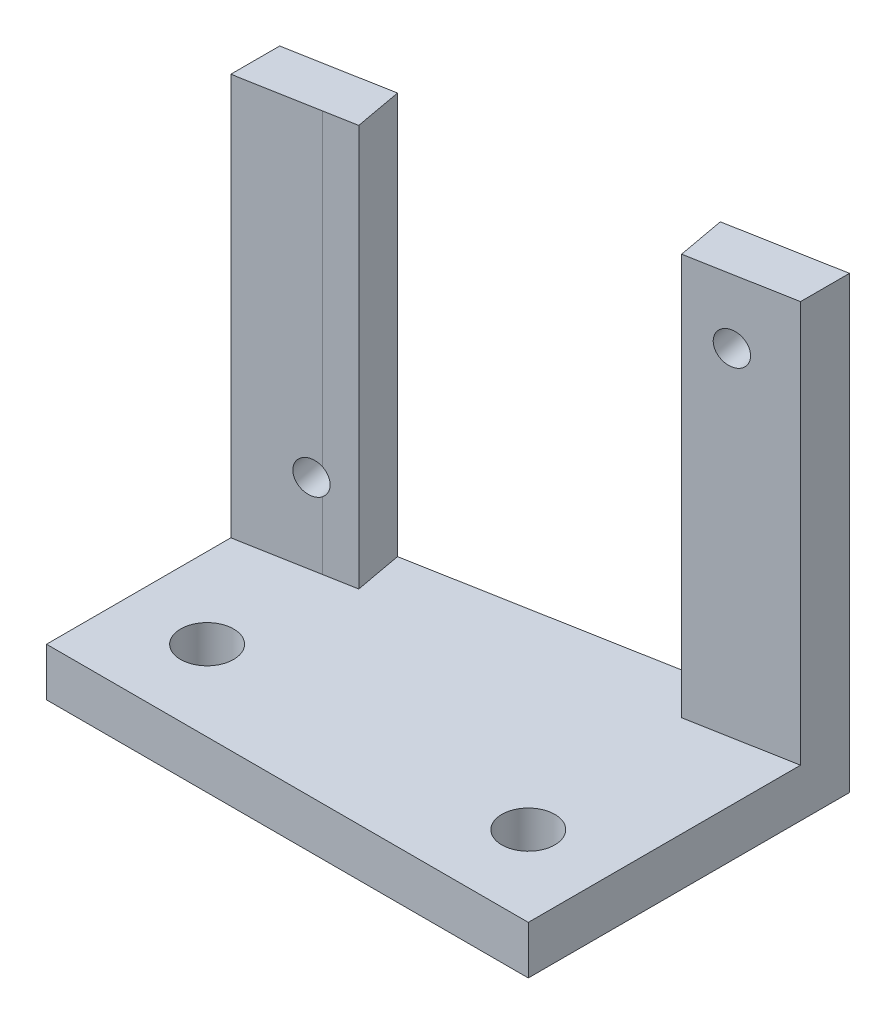
SolidWorks part; units mm, degrees
ref_plane "Ebene vorne" through (0, 0, 0) normal (0, 0, 1) x (1, 0, 0)
ref_plane "Ebene oben" through (0, 0, 0) normal (0, 1, 0) x (1, 0, 0)
ref_plane "Ebene rechts" through (0, 0, 0) normal (1, 0, 0) x (0, 0, -1)
sketch "Sketch1" plane through (0, 0, 0) normal (0, 1, 0) x (1, 0, 0)
  line L5 (-15, -5) -> (15, -5)
  line L6 (-15, -5) -> (-15, 15)
  line L7 (-15, 15) -> (15, 15)
  line L8 (15, -5) -> (15, 15)
  line L9 (-15, -5) -> (15, 15) construction
  line L10 (-15, 15) -> (15, -5) construction
  circle A2 centre (10, 0) radius 1.65
  circle A3 centre (-10, 0) radius 1.65
  point P0 (0, 0)
  dimension "D3" = 20
  dimension "D4" = 3.3
  dimension "D5" = 3.3
  dimension "D1" = 5
  dimension "D2" = 30
  dimension "D6" = 20
  dimension "D7" = 10
extrude "Extrude1" add sketch "Sketch1" along normal blind 3
sketch "Sketch3" plane through (0, 3, 0) normal (0, 1, 0) x (1, 0, 0)
  line L0 (15, 15) -> (-15, 9.5177)
  line L1 (15, 15) -> (15.5393, 12.0489)
  line L2 (-15, 9.5177) -> (-14.4607, 6.5666)
  line L3 (15.5393, 12.0489) -> (-14.4607, 6.5666)
  line L4 (-15, 15) -> (-15, -5) construction
  line L5 (15, 15) -> (15, 11.9503)
  line L6 (15, -5) -> (15, 15) construction
  line L7 (-10.1714, 7.3504) -> (-15, 6.478)
  line L8 (-15, 6.478) -> (-15, 9.5177)
  line L9 (-15, 9.5177) -> (-15, 6.478)
  line M5 (15, -5) -> (15, 15)
  line M7 (-15, 15) -> (-15, -5)
  dimension "D1" = 3
extrude "Extrude2" add sketch "Sketch3" along normal blind 25 contours L7 L3 L0 L2 M5 | L7 L2 M7
sketch "Sketch4" plane through (0, 3, 0) normal (0, 1, 0) x (1, 0, 0)
  line L0 (-15, 9.5177) -> (-15, 15)
  line L1 (-15, 15) -> (15, 15)
  line L2 (15, 15) -> (-15, 9.5177)
extrude "Extrude3" cut sketch "Sketch4" against normal blind 25
sketch "Sketch5" plane through (-1.6285, 0, -8.9116) normal (0.1798, 0, 0.9837) x (0.9837, 0, -0.1798)
  line L0 (16.9039, 28) -> (-8.6844, 28) construction
  line L2 (-6.7362, 28) -> (10.5399, 28)
  line L3 (-6.7362, 28) -> (-6.7362, 3)
  line L4 (-6.7362, 3) -> (10.5399, 3)
  line L5 (10.5399, 28) -> (10.5399, 3)
  circle A0 centre (-9.2686, 8) radius 1
  circle A1 centre (13.2314, 24) radius 1
  dimension "D1" = 2
  dimension "D2" = 2
  dimension "D3" = 22.5
  dimension "D4" = 16
  dimension "D5" = 4
extrude "Extrude4" cut sketch "Sketch5" against normal blind 25
